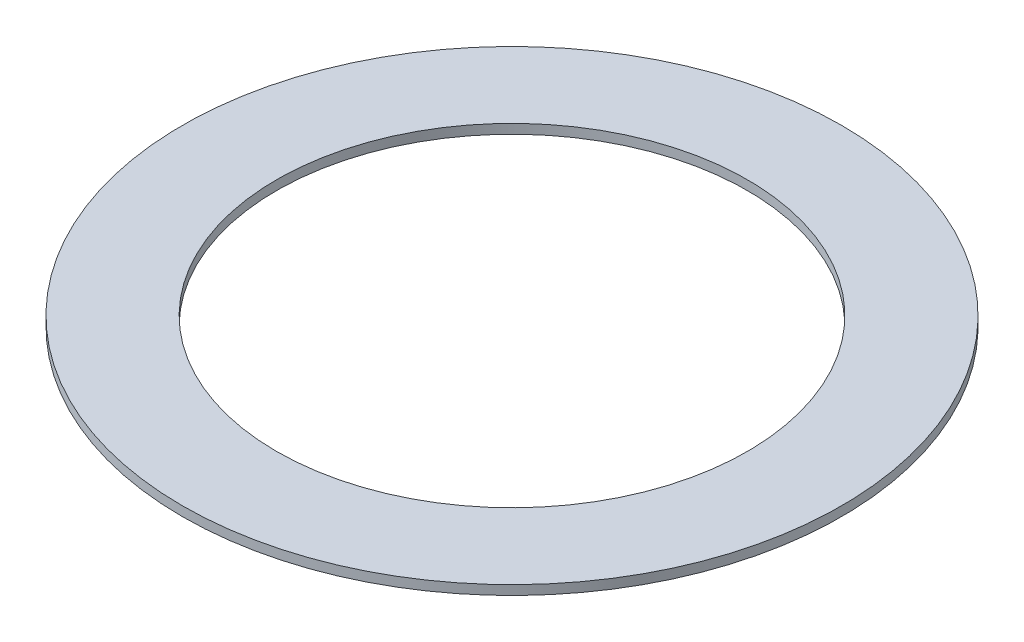
SolidWorks part; units mm, degrees
ref_plane "Front" through (0, 0, 0) normal (0, 0, 1) x (1, 0, 0)
ref_plane "Top" through (0, 0, 0) normal (0, 1, 0) x (1, 0, 0)
ref_plane "Right" through (0, 0, 0) normal (1, 0, 0) x (0, 0, -1)
other "Configuration Table"
sketch "Esquisse1" plane through (0, 0, 0) normal (0, 1, 0) x (1, 0, 0)
  circle A0 centre (0, 0) radius 12.5
  circle A1 centre (0, 0) radius 17.5
  dimension "D1" = 25
  dimension "D2" = 35
extrude "Boss.-Extru.1" add sketch "Esquisse1" along normal blind 0.5
